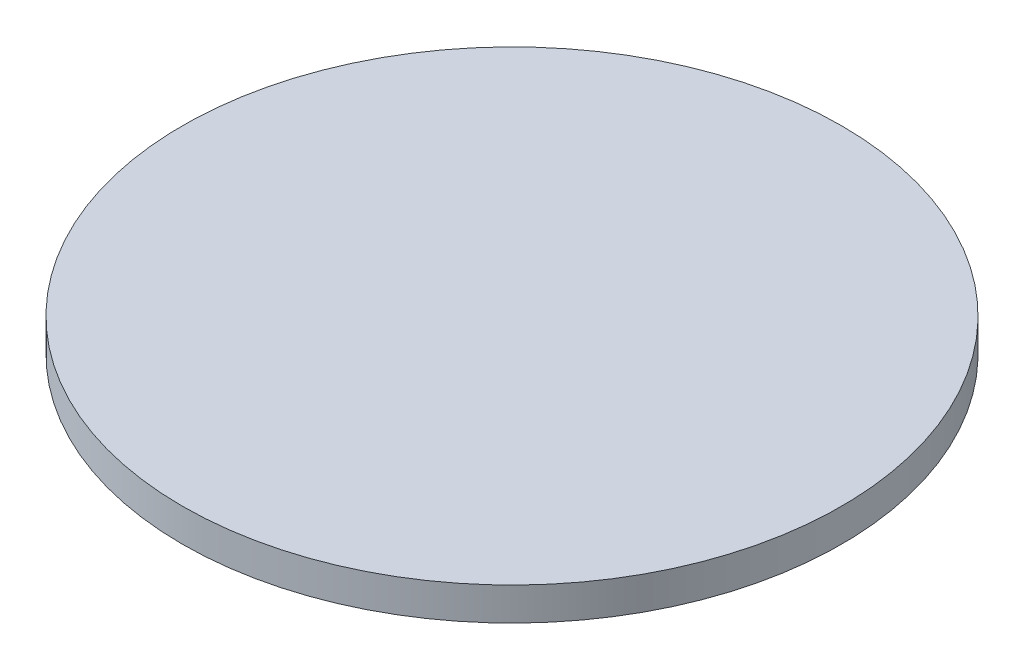
SolidWorks part; units mm, degrees
ref_plane "Front Plane" through (0, 0, 0) normal (0, 0, 1) x (1, 0, 0)
ref_plane "Top Plane" through (0, 0, 0) normal (0, 1, 0) x (1, 0, 0)
ref_plane "Right Plane" through (0, 0, 0) normal (1, 0, 0) x (0, 0, -1)
other "Configuration Table"
sketch "Sketch1" plane through (0, 0, 0) normal (0, 1, 0) x (1, 0, 0)
  circle A0 centre (0, 0) radius 30
extrude "KOLA330_kapak_D60" add sketch "Sketch1" along normal blind 3 from offset 112 separate body
